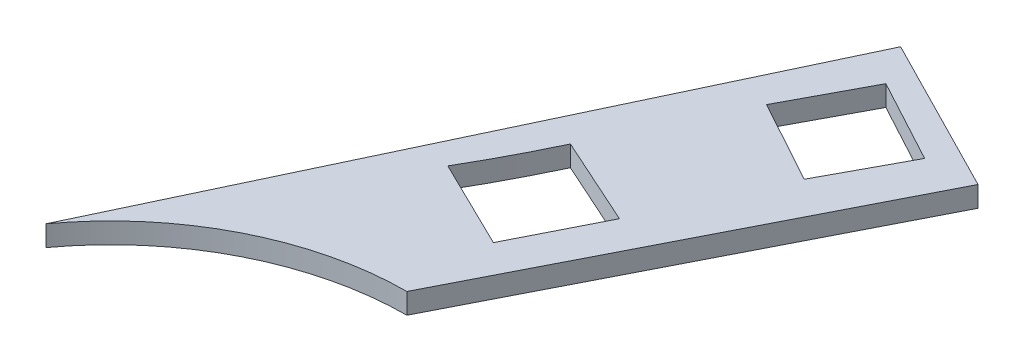
SolidWorks part; units mm, degrees
ref_plane "Front Plane" through (0, 0, 0) normal (0, 0, 1) x (1, 0, 0)
ref_plane "Top Plane" through (0, 0, 0) normal (0, 1, 0) x (1, 0, 0)
ref_plane "Right Plane" through (0, 0, 0) normal (1, 0, 0) x (0, 0, -1)
sketch "Sketch2" plane through (0, 39.7893, 0) normal (0, 1, 0) x (1, 0, 0)
  line L0 (-62.9348, 31.149) -> (-36.827, 82.3346)
  line L1 (-36.827, 82.3346) -> (-58.2065, 93.2394)
  line L2 (-58.2065, 93.2394) -> (-95.2855, 14.6558)
  circle A0 centre (-62.9348, -8.851) radius 40 construction
  arc A4 (-62.9348, 31.149) -> (-95.2855, 14.6558) centre (-62.8289, -9.0325) ccw
  dimension "D3" = 24
  dimension "D4" = 40.1817
  dimension "D1" = 86.8921
  dimension "D2" = 51.1856
extrude "Boss-Extrude3" add sketch "Sketch2" along normal blind 1 and the other way blind 1.7911 separate body
sketch "Sketch14" plane through (0, 40.7893, 0) normal (0, 1, 0) x (1, 0, 0)
  line L11 (-60.4975, 77.3856) -> (-49.1986, 71.1867)
  line L12 (-49.1986, 71.1867) -> (-43.4916, 81.7775)
  line L13 (-43.4916, 81.7775) -> (-54.8782, 87.9165)
  line L14 (-60.4975, 77.3856) -> (-54.8782, 87.9165)
extrude "Cut-Extrude4" cut sketch "Sketch14" against normal through all
sketch "Sketch15" plane through (0, 40.7893, 0) normal (0, 1, 0) x (1, 0, 0)
  line L0 (-69.1581, 59.5031) -> (-57.0791, 54.0598)
  line L1 (-57.0791, 54.0598) -> (-62.8058, 42.725)
  line L2 (-62.8058, 42.725) -> (-74.8833, 48.6315)
  arc A0 (-74.8833, 48.6315) -> (-69.1581, 59.5031) centre (-194.0323, 118.3207) ccw
  dimension "D1" = 138.0329
extrude "Cut-Extrude7" cut sketch "Sketch15" against normal through all
